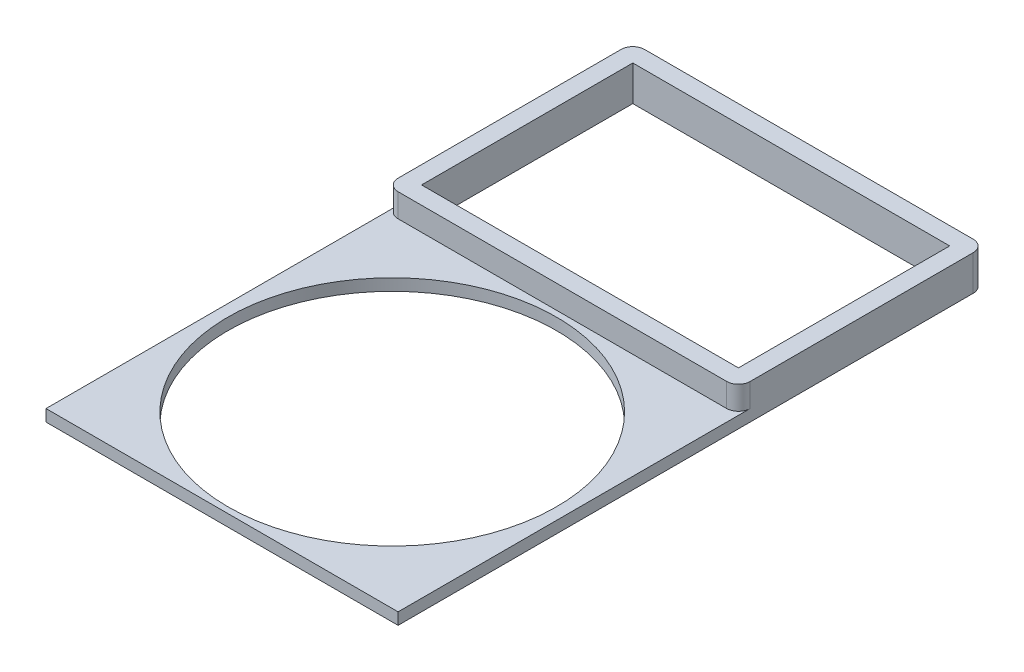
SolidWorks part; units mm, degrees
ref_plane "Plan de face" through (0, 0, 0) normal (0, 0, 1) x (1, 0, 0)
ref_plane "Plan de dessus" through (0, 0, 0) normal (0, 1, 0) x (1, 0, 0)
ref_plane "Plan de droite" through (0, 0, 0) normal (1, 0, 0) x (0, 0, -1)
sketch "Esquisse1" plane through (0, 0, 0) normal (0, 1, 0) x (1, 0, 0)
  line L0 (0, 0) -> (0, 14.5) construction
  line L1 (15, -25) -> (-15, -25)
  line L2 (15, -25) -> (15, 25)
  line L3 (15, 25) -> (-15, 25)
  line L4 (-15, -25) -> (-15, 25)
  line L5 (15, -25) -> (-15, 25) construction
  line L6 (15, 25) -> (-15, -25) construction
  line L7 (-13.5, 5.5) -> (13.5, 5.5)
  line L8 (-13.5, 5.5) -> (-13.5, 23.5)
  line L9 (-13.5, 23.5) -> (13.5, 23.5)
  line L10 (13.5, 5.5) -> (13.5, 23.5)
  line L11 (-13.5, 5.5) -> (13.5, 23.5) construction
  line L12 (-13.5, 23.5) -> (13.5, 5.5) construction
  line L13 (0, 0) -> (0, -25) construction
  circle A0 centre (0, -10.5) radius 14
  point P0 (0, 0)
  point P6 (0, 14.5)
  dimension "D6" = 28
  dimension "D7" = 14.5
  dimension "D1" = 30
  dimension "D2" = 50
  dimension "D3" = 27
  dimension "D4" = 18
  dimension "D5" = 1.5
extrude "Boss.-Extru.1" add sketch "Esquisse1" along normal blind 1
sketch "Esquisse2" plane through (0, 1, 0) normal (0, 1, 0) x (1, 0, 0)
  line L0 (15, -25) -> (15, 25) construction
  line L1 (-15, 25) -> (15, 25)
  line L2 (-15, 25) -> (-15, 4)
  line L3 (-15, 4) -> (15, 4)
  line L4 (15, 25) -> (15, 4)
  line L6 (-13.5, 23.5) -> (13.5, 23.5)
  line L7 (-13.5, 23.5) -> (-13.5, 5.5)
  line L8 (-13.5, 5.5) -> (13.5, 5.5)
  line L9 (13.5, 23.5) -> (13.5, 5.5)
  dimension "D1" = 21
extrude "Boss.-Extru.2" add sketch "Esquisse2" along normal blind 2
fillet "Congé1" radius 1 4 edges at (-15, 1.5, -25) (15, 1.5, -25)
